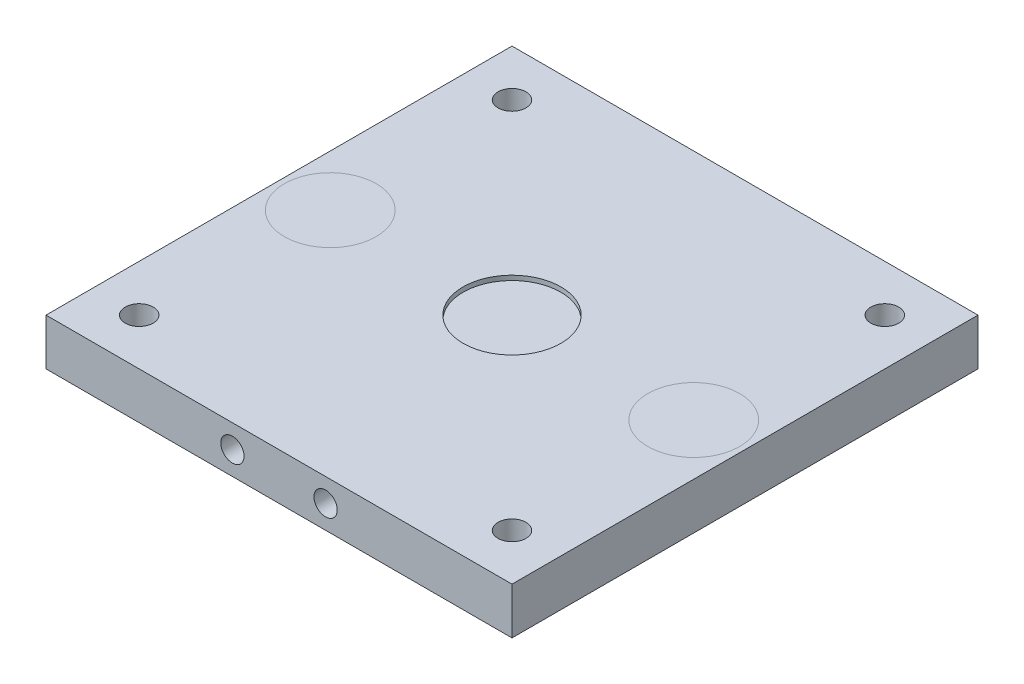
SolidWorks part; units mm, degrees
material "6061-T4 (SS)"
ref_plane "Front Plane" through (0, 0, 0) normal (0, 0, 1) x (1, 0, 0)
ref_plane "Top Plane" through (0, 0, 0) normal (0, 1, 0) x (1, 0, 0)
ref_plane "Right Plane" through (0, 0, 0) normal (1, 0, 0) x (0, 0, -1)
sketch "Sketch1" plane through (0, 0, 0) normal (0, 1, 0) x (1, 0, 0)
  line L1 (50, 50) -> (-50, 50)
  line L2 (50, 50) -> (50, -50)
  line L3 (50, -50) -> (-50, -50)
  line L4 (-50, 50) -> (-50, -50)
  line L5 (50, 50) -> (-50, -50) construction
  line L6 (50, -50) -> (-50, 50) construction
  point P0 (0, 0)
  dimension "D1" = 100
  dimension "D2" = 100
extrude "base" add sketch "Sketch1" along normal blind 10
sketch "Sketch2" plane through (0, 10, 0) normal (0, 1, 0) x (1, 0, 0)
  circle A0 centre (0, 0) radius 10.5
  dimension "D1" = 21
extrude "load cell cut" cut sketch "Sketch2" against normal blind 1 contours A0
sketch "post positioning points" plane through (0, 10, 0) normal (0, 1, 0) x (1, 0, 0)
  line L0 (-50, 50) -> (-50, -50) construction
  line L1 (-50, -50) -> (50, -50) construction
  line L2 (50, -50) -> (50, 50) construction
  line L3 (50, 50) -> (-50, 50) construction
  point P0 (-10, -40)
  point P5 (50, 40)
  point P6 (-10, 40)
  point P7 (10, 40)
  point P8 (10, -40)
  point P9 (75, -40)
  point P10 (-50, 40)
  dimension "D1" = 40
  dimension "D2" = 10
  dimension "D3" = 40
  dimension "D4" = 10
  dimension "D5" = 85
  dimension "D7" = 60
  dimension "D6" = 60
sketch "Sketch6" plane through (0, 0, -50) normal (0, 0, 1) x (1, 0, 0)
  line L0 (-50, 0) -> (50, 0) construction
  line L1 (9, 10) -> (-9, 10)
  line L2 (9, 10) -> (9, 5)
  line L3 (9, 5) -> (-9, 5)
  line L4 (-9, 10) -> (-9, 5)
  line L5 (9, 10) -> (-9, 5) construction
  line L6 (9, 5) -> (-9, 10) construction
  line L7 (-50, 10) -> (50, 10) construction
  point P0 (0, 7.5)
  point P8 (0, 0)
  dimension "D1" = 18
  dimension "D2" = 5
extrude "cut wire" [suppressed] cut sketch "Sketch6" along normal blind 50 contours L4 L3 L2 L1
sketch "Sketch7" plane through (0, 0, -50) normal (0, 0, 1) x (1, 0, 0)
  line L1 (5, 10) -> (-5, 10)
  line L2 (5, 10) -> (5, 0)
  line L3 (5, 0) -> (-5, 0)
  line L4 (-5, 10) -> (-5, 0)
  line L5 (5, 10) -> (-5, 0) construction
  line L6 (5, 0) -> (-5, 10) construction
  line L7 (-50, 0) -> (50, 0) construction
  line L8 (-50, 10) -> (50, 10) construction
  point P0 (0, 5)
  point P8 (0, 0)
  dimension "D1" = 10
  dimension "D2" = 10
extrude "cut wire 2" [suppressed] cut sketch "Sketch7" along normal up to next
fillet "Fillet5" [suppressed] radius 10
fillet "Fillet6" [suppressed] radius 0.1
fillet "Fillet7" [suppressed] radius 5
sketch "Sketch12" plane through (0, 0, 0) normal (0, -1, 0) x (1, 0, 0)
  line L0 (0, 0) -> (50, 0) construction
  line L1 (19.771, 8.1894) -> (-8.1894, 19.771) construction
  line L2 (-8.1894, 19.771) -> (-19.771, -8.1894) construction
  line L3 (-19.771, -8.1894) -> (8.1894, -19.771) construction
  line L4 (8.1894, -19.771) -> (19.771, 8.1894) construction
  line L5 (50, 50) -> (50, -50) construction
  circle A0 centre (0, 0) radius 15.1321 construction
  dimension "D1" = 22.5
  dimension "D2" = 21.4
hole_wizard "Ø5.0mm Dowel Hole1" [suppressed] positions "3DSketch4" profile "Sketch13" hole size "Ø5.0" standard "ANSI Metric"
sketch3d "3DSketch4"
  point P0 (-8.1894, 0, 19.771)
  point P3 (19.771, 0, 8.1894)
  point P6 (8.1894, 0, -19.771)
  point P9 (-19.771, 0, -8.1894)
sketch "Sketch13" plane through (-8.1894, 0, 19.771) normal (1, 0, 0) x (0, 0, -1)
  line L0 (0, 0) -> (0, 5)
  line L1 (0, 5) -> (2.5, 5)
  line L2 (2.5, 5) -> (2.5, 0)
  line L5 (2.5, 0) -> (0, 0)
  line L11 (0, -6.35) -> (0, 107.95) construction
  dimension "Thru Hole Dia." = 5
  dimension "Thru Hole Depth" = 5
fillet "Fillet8" [suppressed] radius 5
sketch "Sketch14" plane through (0, 9, 0) normal (0, 1, 0) x (1, 0, 0)
  circle A0 centre (0, 0) radius 25
  dimension "D1" = 50
split line "Split Line1" [suppressed]
fillet "Fillet9" [suppressed] radius 1
sketch "Sketch15" plane through (0, 0, 0) normal (0, -1, 0) x (-1, 0, 0)
  line L0 (-40, -40) -> (40, -40) construction
  line L1 (40, -40) -> (40, 40) construction
  circle A0 centre (40, -40) radius 3
  circle A1 centre (-40, -40) radius 3
  circle A2 centre (40, 40) radius 3
  circle A3 centre (-40, 40) radius 3
  point P2 (40, 0)
  point P5 (0, -40)
  dimension "D3" = 6
  dimension "D1" = 80
  dimension "D2" = 80
extrude "Cut-Extrude1" cut sketch "Sketch15" against normal up to next
hole_wizard "Ø4.0mm Dowel Hole1" [suppressed] positions "Sketch17" profile "Sketch18" hole size "Ø4.0" standard "ANSI Metric"
sketch "Sketch17" plane through (0, 0, 50) normal (0, 0, 1) x (1, 0, 0)
  line L1 (-50, 10) -> (-50, 0) construction
  line L2 (50, 10) -> (50, 0) construction
  point P0 (-45, 5)
  point P3 (-25, 5)
  point P6 (25, 5)
  point P9 (45, 5)
  dimension "D1" = 25
  dimension "D2" = 5
  dimension "D3" = 25
  dimension "D4" = 5
sketch "Sketch18" plane through (-45, 5, 50) normal (1, 0, 0) x (0, -1, 0)
  line L0 (0, 0) -> (0, 11.2017)
  line L1 (0, 11.2017) -> (2, 10)
  line L2 (2, 10) -> (2, 0)
  line L5 (2, 0) -> (0, 0)
  line L10 (0, 11.2017) -> (-2, 10) construction
  line L11 (0, -6.35) -> (0, 107.95) construction
  dimension "Hole Dia." = 4
  dimension "Hole Depth" = 10
  dimension "Drill Angle" = 118
cosmetic thread "Cosmetic Thread1" [suppressed] parameters "D2"=4
cosmetic thread "Cosmetic Thread2" [suppressed] parameters "D2"=5
cosmetic thread "Cosmetic Thread3" [suppressed] parameters "D2"=4
cosmetic thread "Cosmetic Thread4" [suppressed] parameters "D2"=4
cosmetic thread "Cosmetic Thread9" [suppressed] parameters "D2"=5
cosmetic thread "Cosmetic Thread11" [suppressed] parameters "D2"=5
cosmetic thread "Cosmetic Thread13" [suppressed] parameters "D2"=5
mirror "Mirror1" [suppressed] about plane through (0, 0, 0) normal (0, 0, 1)
cosmetic thread "Cosmetic Thread5" [suppressed] parameters "D2"=5
cosmetic thread "Cosmetic Thread6" [suppressed] parameters "D2"=4
cosmetic thread "Cosmetic Thread7" [suppressed] parameters "D2"=4
cosmetic thread "Cosmetic Thread8" [suppressed] parameters "D2"=4
cosmetic thread "Cosmetic Thread10" [suppressed] parameters "D2"=5
cosmetic thread "Cosmetic Thread12" [suppressed] parameters "D2"=5
cosmetic thread "Cosmetic Thread14" [suppressed] parameters "D2"=5
cosmetic thread "Cosmetic Thread15" [suppressed] parameters "D2"=5
cosmetic thread "Cosmetic Thread16" [suppressed] parameters "D2"=5
cosmetic thread "Cosmetic Thread17" [suppressed] parameters "D2"=5
cosmetic thread "Cosmetic Thread18" [suppressed] parameters "D2"=5
sketch "Sketch21" plane through (0, 0, -50) normal (0, 0, -1) x (-1, 0, 0)
  circle A0 centre (-10, 5) radius 2.5
  circle A1 centre (10, 5) radius 2.5
  dimension "D1" = 5
  dimension "D2" = 5
extrude "Cut-Extrude2" cut sketch "Sketch21" against normal blind 10
mirror "Mirror2" about plane through (0, 0, 0) normal (0, 0, 1) of "Cut-Extrude2"
sketch "Sketch22" plane through (0, 10, 0) normal (0, 1, 0) x (1, 0, 0)
  circle A0 centre (40, -40) radius 4
  circle A1 centre (-40, -40) radius 4
  circle A2 centre (-40, 40) radius 4
  circle A3 centre (40, 40) radius 4
  dimension "D1" = 8
extrude "Cut-Extrude3" [suppressed] cut sketch "Sketch22" against normal through all
sketch "Sketch23" plane through (0, 10, 0) normal (0, 1, 0) x (1, 0, 0)
  line L0 (39, 0) -> (-39, 0) construction
  circle A0 centre (39, 0) radius 9.85
  circle A1 centre (-39, 0) radius 9.85
  point P4 (0, 0)
  dimension "D1" = 19.7
  dimension "D2" = 19.7
  dimension "D3" = 78
split line "Split Line2"
equation "\"D2@post positioning points\"=10"
equation "\"D3@post positioning points\"=\"D1@post positioning points\""
equation "\"D4@post positioning points\"=\"D2@post positioning points\""
equation "\"D1@base\"=10"
equation "\"D1@load cell cut\"=5"
equation "\"D2@Sketch6\"=5"
